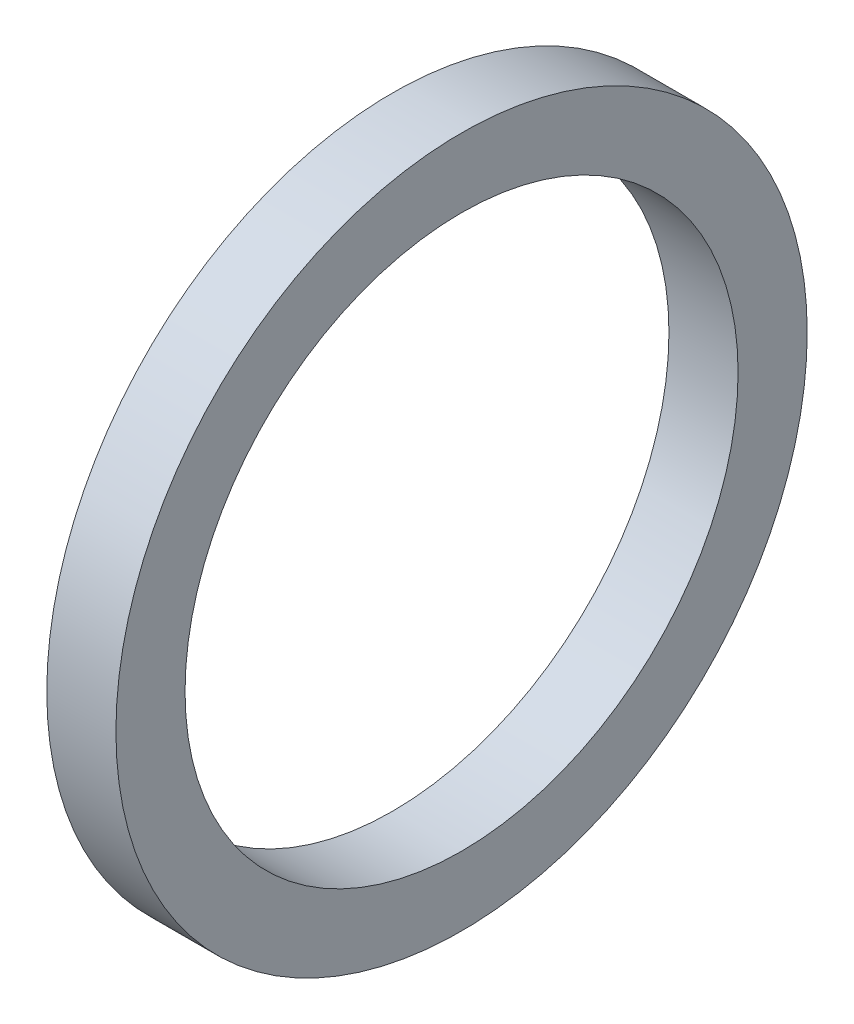
SolidWorks part; units mm, degrees
ref_plane "Front Plane" through (0, 0, 0) normal (0, 0, 1) x (1, 0, 0)
ref_plane "Top Plane" through (0, 0, 0) normal (0, 1, 0) x (1, 0, 0)
ref_plane "Right Plane" through (0, 0, 0) normal (1, 0, 0) x (0, 0, -1)
sketch "Sketch1" plane through (0, 0, 0) normal (0, 1, 0) x (1, 0, 0)
  line L0 (0, 0) -> (40.4571, 0) construction
  line L2 (0, 20) -> (5, 20)
  line L3 (0, 20) -> (0, 25)
  line L4 (0, 25) -> (5, 25)
  line L5 (5, 20) -> (5, 25)
  dimension "D1" = 40
  dimension "D2" = 50
  dimension "D3" = 5
revolve "Revolve1" add sketch "Sketch1" angle 360 about L0
